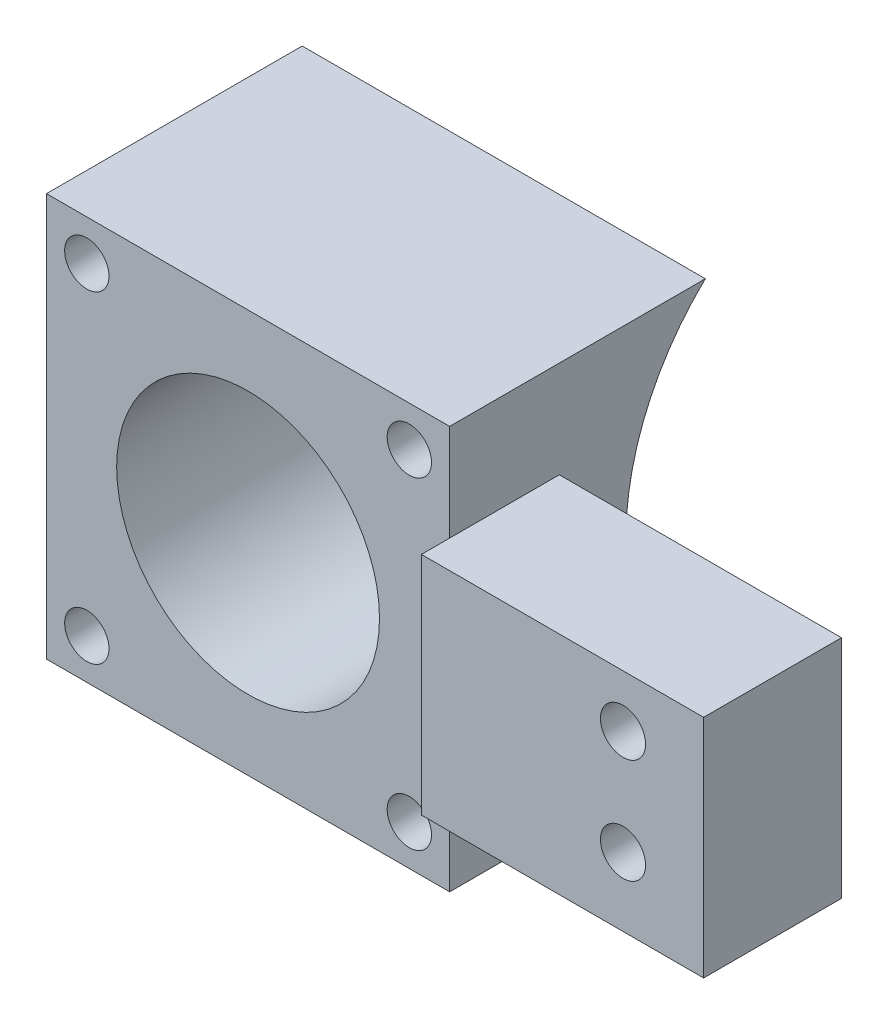
SolidWorks part; units mm, degrees
material "Delrin 2700 NC010, Low Viscosity Acetal Copolymer (SS)"
ref_plane "Front Plane" through (0, 0, 0) normal (0, 0, 1) x (1, 0, 0)
ref_plane "Top Plane" through (0, 0, 0) normal (0, 1, 0) x (1, 0, 0)
ref_plane "Right Plane" through (0, 0, 0) normal (1, 0, 0) x (0, 0, -1)
sketch "Sketch1" plane through (0, 0, 0) normal (0, 0, 1) x (1, 0, 0)
  line L1 (-25, 23) -> (25, 23)
  line L2 (-25, 23) -> (-25, -27)
  line L3 (-25, -27) -> (25, -27)
  line L4 (25, 23) -> (25, -27)
  line L5 (-25, 23) -> (25, -27) construction
  line L6 (-25, -27) -> (25, 23) construction
  circle A0 centre (0, -2) radius 16.3
  circle A1 centre (-20, 18) radius 2.75
  circle A2 centre (20, 18) radius 2.75
  circle A3 centre (20, -22) radius 2.75
  circle A4 centre (-20, -22) radius 2.75
  point P0 (0, -2)
  dimension "D4" = 32.6
  dimension "D6" = 5.5
  dimension "D1" = 2
  dimension "D2" = 50
  dimension "D3" = 50
  dimension "D5" = 20
  dimension "D7" = 20
  dimension "D9" = 20
  dimension "D10" = 20
extrude "Boss-Extrude1" add sketch "Sketch1" along normal blind 53.6
sketch "Sketch2" plane through (0, 0, 0) normal (1, 0, 0) x (0, 0, -1)
  circle A0 centre (0, 0) radius 31.75
  dimension "D1" = 63.5
extrude "Cut-Extrude1" cut sketch "Sketch2" against normal through all and the other way through all
sketch "Sketch3" plane through (-25, 0, 0) normal (-1, 0, 0) x (0, 0, 1)
  line L3 (53.6, 23) -> (21.8875, 23)
  line L4 (16.7052, -27) -> (53.6, -27)
  line L5 (53.6, -27) -> (53.6, 23)
  line L6 (53.6, 23) -> (21.8875, 23)
  line L7 (16.7052, -27) -> (53.6, -27)
  line L8 (53.6, -27) -> (53.6, 23)
  arc A1 (16.7052, -27) -> (21.8875, 23) centre (0, 0) ccw
  arc A2 (16.7052, -27) -> (21.8875, 23) centre (0, 0) ccw
  dimension "D1" = 0
sketch "Sketch4" plane through (25, 0, 0) normal (1, 0, 0) x (0, 0, -1)
  line L3 (-53.6, -27) -> (-16.7052, -27)
  line L4 (-21.8875, 23) -> (-53.6, 23)
  line L5 (-53.6, 23) -> (-53.6, -27)
  line L8 (-53.6, 11) -> (-53.6, -17)
  line L12 (-53.6, 11) -> (-29.7836, 11)
  line L13 (-53.6, 23) -> (-21.8875, 23) construction
  line L14 (0, 0) -> (-85.4701, 0) construction
  line L15 (-53.6, -11) -> (-29.7836, -11) construction
  line L16 (-53.6, -17) -> (-26.8153, -17)
  arc A0 (-21.8875, 23) -> (-16.7052, -27) centre (0, 0) ccw construction
  arc A1 (-21.8875, 23) -> (-16.7052, -27) centre (0, 0) ccw
  arc A2 (-29.7836, 11) -> (-26.8153, -17) centre (0, 0) ccw
  dimension "D3" = 12
  dimension "D4" = 6
  dimension "D1" = 0
extrude "Boss-Extrude3" add sketch "Sketch4" along normal blind 35
sketch "Sketch12" plane through (0, 0, 53.6) normal (0, 0, 1) x (1, 0, 0)
  line L6 (60, 11) -> (60, -17) construction
  line L7 (60, 11) -> (25, 11) construction
  line L8 (60, -17) -> (25, -17) construction
  line L9 (60, 11) -> (60, -17)
  line L10 (60, 11) -> (25, 11)
  line L11 (60, -17) -> (25, -17)
  line L12 (25, 11) -> (25, -17)
sketch "Sketch10" plane through (0, 0, 53.6) normal (0, 0, 1) x (1, 0, 0)
  line L0 (50, 4.5) -> (50, -8.5) construction
  line L1 (60, -2) -> (0, -2) construction
  line L2 (60, 11) -> (60, -17) construction
  line L3 (25, -27) -> (25, -17) construction
  line L4 (60, 11) -> (60, -17) construction
  line L5 (50, 22) -> (50, -27) construction
  line L6 (-25, -27) -> (25, -27) construction
  circle A0 centre (50, 4.5) radius 2.8
  circle A1 centre (50, -8.5) radius 2.8
  point P8 (50, -2)
  point P10 (60, -3)
  dimension "D1" = 5.6
  dimension "D2" = 1
  dimension "D3" = 13
  dimension "D4" = 25
extrude "Cut-Extrude6" cut sketch "Sketch10" against normal blind 10 and the other way through all
sketch "Sketch13" plane through (60, 0, 0) normal (1, 0, 0) x (0, 0, -1)
  line L0 (-29.7836, 11) -> (-40, 11)
  line L1 (-29.7836, 11) -> (-53.6, 11) construction
  line L2 (-40, 11) -> (-40, -17)
  line L3 (-53.6, -17) -> (-26.8153, -17) construction
  line L4 (-40, -17) -> (-26.8153, -17)
  arc A0 (-29.7836, 11) -> (-26.8153, -17) centre (0, 0) ccw construction
  arc A1 (-29.7836, 11) -> (-26.8153, -17) centre (0, 0) ccw
  dimension "D1" = 40
extrude "Cut-Extrude8" cut sketch "Sketch13" against normal up to surface (35 mm away) up to face at (25, 17.1131, 39.8897)
sketch "Sketch14" [suppressed] plane through (60, 0, 0) normal (1, 0, 0) x (0, 0, -1)
  line L0 (-33.6, 11) -> (-33.6, -17) construction
  line L1 (-45.6, -17) -> (-33.6, -17) construction
  line L2 (-45.6, -17) -> (-45.6, 11) construction
  line L3 (-33.6, 11) -> (-45.6, 11) construction
  line L4 (-33.6, 11) -> (-33.6, -17)
  line L5 (-45.6, -17) -> (-33.6, -17)
  line L6 (-45.6, -17) -> (-45.6, 11) construction
  line L7 (-33.6, 11) -> (-45.6, 11)
  line L8 (-33.6, -3) -> (-36.6, -3) construction
  line L9 (-36.6, -3) -> (-36.6, 11) construction
  line L10 (-36.6, -3) -> (-36.6, -17) construction
  line L11 (-36.6, 4) -> (-36.6, -10)
  arc A0 (-45.6, 11) -> (-36.6, 4) centre (-45.6, 1.7143) cw
  arc A1 (-45.6, -17) -> (-36.6, -10) centre (-45.6, -7.7143) ccw
  dimension "D1" = 3
extrude "Cut-Extrude9" [suppressed] cut sketch "Sketch14" against normal up to surface (35 mm away)
sketch "Sketch16" plane through (0, 0, 53.6) normal (0, 0, 1) x (1, 0, 0)
  line L0 (60, 11) -> (60, -17) construction
  line L1 (60, -17) -> (25, -17) construction
  line L2 (60, 11) -> (25, 11) construction
  line L3 (25, 11) -> (25, -17) construction
  line L4 (60, 11) -> (60, -17)
  line L5 (60, -17) -> (25, -17)
  line L6 (60, 11) -> (25, 11)
  line L7 (25, 11) -> (25, -17)
  circle A0 centre (50, 4.5) radius 2.8 construction
  circle A1 centre (50, -8.5) radius 2.8 construction
  circle A2 centre (50, 4.5) radius 2.8
  circle A3 centre (50, -8.5) radius 2.8
extrude "Boss-Extrude4" add sketch "Sketch16" along normal blind 3.5
